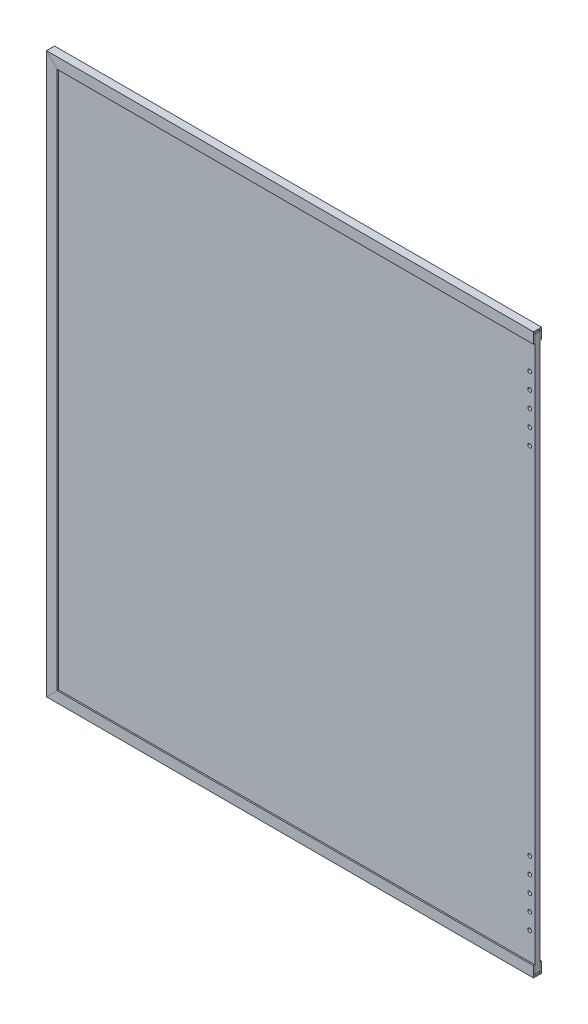
SolidWorks part; units mm, degrees
material "Plywood"
ref_plane "Front Plane" through (0, 0, 0) normal (0, 0, 1) x (1, 0, 0)
ref_plane "Top Plane" through (0, 0, 0) normal (0, 1, 0) x (1, 0, 0)
ref_plane "Right Plane" through (0, 0, 0) normal (1, 0, 0) x (0, 0, -1)
sketch "Shelf opening" plane through (0, 0, 0) normal (0, 0, 1) x (1, 0, 0)
  line L1 (0, 0) -> (577.85, 0)
  line L2 (0, 0) -> (0, 635)
  line L3 (0, 635) -> (577.85, 635)
  line L4 (577.85, 0) -> (577.85, 635)
  dimension "D1" = 577.85
  dimension "D2" = 635
sketch "Sketch2" plane through (0, 0, 0) normal (0, 0, 1) x (1, 0, 0)
  line L0 (577.85, 0) -> (577.85, 635) construction
  line L1 (3.175, 647.7) -> (577.85, 647.7)
  line L2 (3.175, 647.7) -> (3.175, -12.7)
  line L3 (3.175, -12.7) -> (577.85, -12.7)
  line L4 (577.85, 647.7) -> (577.85, -12.7)
  line L5 (0, 635) -> (577.85, 635) construction
  line L6 (0, 0) -> (0, 635) construction
  line L7 (0, 0) -> (577.85, 0) construction
  dimension "D1" = 12.7
  dimension "D2" = 3.175
  dimension "D3" = 12.7
extrude "Frame outer dimensions" add sketch "Sketch2" along normal mid plane 9.525
sketch "Sketch3" plane through (0, 0, 4.7625) normal (0, 0, 1) x (1, 0, 0)
  line L0 (577.85, -12.7) -> (577.85, 647.7) construction
  line L1 (577.85, 635) -> (15.875, 635)
  line L2 (577.85, 635) -> (577.85, 0)
  line L3 (577.85, 0) -> (15.875, 0)
  line L4 (15.875, 635) -> (15.875, 0)
  line L5 (577.85, 647.7) -> (3.175, 647.7) construction
  line L6 (3.175, 647.7) -> (3.175, -12.7) construction
  line L7 (3.175, -12.7) -> (577.85, -12.7) construction
  dimension "D1" = 12.7
  dimension "D2" = 12.7
  dimension "D3" = 12.7
extrude "Frame inner dimensions" cut sketch "Sketch3" against normal through all
sketch "Sketch4" plane through (0, 0, 0) normal (0, 0, 1) x (1, 0, 0)
  line L0 (577.85, 635) -> (577.85, 647.7) construction
  line L1 (577.85, 646.1125) -> (4.7625, 646.1125)
  line L2 (577.85, 646.1125) -> (577.85, -11.1125)
  line L3 (577.85, -11.1125) -> (4.7625, -11.1125)
  line L4 (4.7625, 646.1125) -> (4.7625, -11.1125)
  line L5 (577.85, 647.7) -> (3.175, 647.7) construction
  line L6 (3.175, 647.7) -> (3.175, -12.7) construction
  line L7 (3.175, -12.7) -> (577.85, -12.7) construction
  dimension "D1" = 1.5875
  dimension "D2" = 1.5875
  dimension "D3" = 1.5875
extrude "Frame profile" cut sketch "Sketch4" along normal offset from surface 1.5875 and the other way offset from surface (3.175 mm away) 1.5875 up to face at (293.6875, 317.5, 4.7625) other way up to face at (293.6875, 317.5, -4.7625)
sketch "Frame sections" plane through (0, 0, 4.7625) normal (0, 0, 1) x (1, 0, 0)
  line L0 (3.175, 647.7) -> (15.875, 635)
  line L1 (3.175, -12.7) -> (15.875, 0)
split "Frame section split" trim tools "Frame sections" bodies to split 103 resulting bodies 105 106 107
sketch "Sketch5" plane through (0, 0, 0) normal (0, 0, 1) x (1, 0, 0)
  line L0 (577.85, 635) -> (577.85, 647.7) construction
  line L1 (577.85, 644.525) -> (6.35, 644.525)
  line L2 (577.85, 644.525) -> (577.85, -9.525)
  line L3 (577.85, -9.525) -> (6.35, -9.525)
  line L4 (6.35, 644.525) -> (6.35, -9.525)
  line L5 (4.7625, 646.1125) -> (577.85, 646.1125) construction
  line L6 (4.7625, -11.1125) -> (4.7625, 646.1125) construction
  line L7 (577.85, -11.1125) -> (4.7625, -11.1125) construction
  dimension "D1" = 1.5875
  dimension "D2" = 1.5875
  dimension "D3" = 1.5875
  dimension "D4" = 571.5
  dimension "D5" = 654.05
extrude "Door panel" add sketch "Sketch5" along normal mid plane 5.588 separate body
sketch "Hinge positions" plane through (0, 0, 2.794) normal (0, 0, 1) x (1, 0, 0)
  line L0 (577.85, -9.525) -> (577.85, 644.525) construction
  line L1 (577.85, 612.775) -> (565.15, 612.775)
  line L2 (577.85, 612.775) -> (577.85, 517.525)
  line L3 (577.85, 517.525) -> (565.15, 517.525)
  line L4 (565.15, 612.775) -> (565.15, 517.525)
  line L5 (565.15, 117.475) -> (577.85, 117.475)
  line L6 (565.15, 117.475) -> (565.15, 22.225)
  line L7 (565.15, 22.225) -> (577.85, 22.225)
  line L8 (577.85, 117.475) -> (577.85, 22.225)
  line L10 (0, 0) -> (577.85, 0) construction
  line L11 (0, 635) -> (577.85, 635) construction
  dimension "D1" = 95.25
  dimension "D2" = 12.7
  dimension "D3" = 22.225
  dimension "D4" = 22.225
  dimension "D5" = 495.3
sketch "Sketch8" plane through (0, 0, 2.794) normal (0, 0, 1) x (1, 0, 0)
  line L0 (565.15, 69.85) -> (577.85, 69.85) construction
  line L2 (565.15, 117.475) -> (565.15, 22.225) construction
  line L3 (577.85, 117.475) -> (577.85, 22.225) construction
  line L4 (565.15, 565.15) -> (577.85, 565.15) construction
  line L6 (565.15, 612.775) -> (565.15, 517.525) construction
  line L7 (577.85, 612.775) -> (577.85, 517.525) construction
  point P0 (571.5, 31.75)
  point P11 (571.5, 50.8)
  point P12 (571.5, 69.85)
  point P13 (571.5, 88.9)
  point P14 (571.5, 107.95)
  point P15 (571.5, 546.1)
  point P16 (571.5, 565.15)
  point P17 (571.5, 584.2)
  point P18 (571.5, 603.25)
  point P19 (571.5, 527.05)
  dimension "D3" = 19.05
  dimension "D1" = 5
  dimension "D2" = 2
hole_wizard "#8 Clearance Hole1" positions "Sketch8" profile "Sketch9" hole size "#8" standard "ANSI Inch" end condition through all
sketch "Sketch9" plane through (571.5, 31.75, 2.794) normal (1, 0, 0) x (0, -1, 0)
  line L0 (0, 0) -> (0, 7.5565)
  line L1 (0, 7.5565) -> (2.2479, 7.5565)
  line L2 (2.2479, 7.5565) -> (2.2479, 0)
  line L5 (2.2479, 0) -> (0, 0)
  line L11 (0, -6.35) -> (0, 107.95) construction
  dimension "Thru Hole Dia." = 4.4958
  dimension "Thru Hole Depth" = 7.5565
mirror "Mirror1" about plane through (0, 0, 0) normal (1, 0, 0) of bodies 105 106 107 108
delete or keep bodies "Body-Delete/Keep 1" type keep bodies bodies 105 106 107 108
delete or keep bodies "Body-Delete/Keep 2" [suppressed] type keep bodies bodies 109 110 111 112
